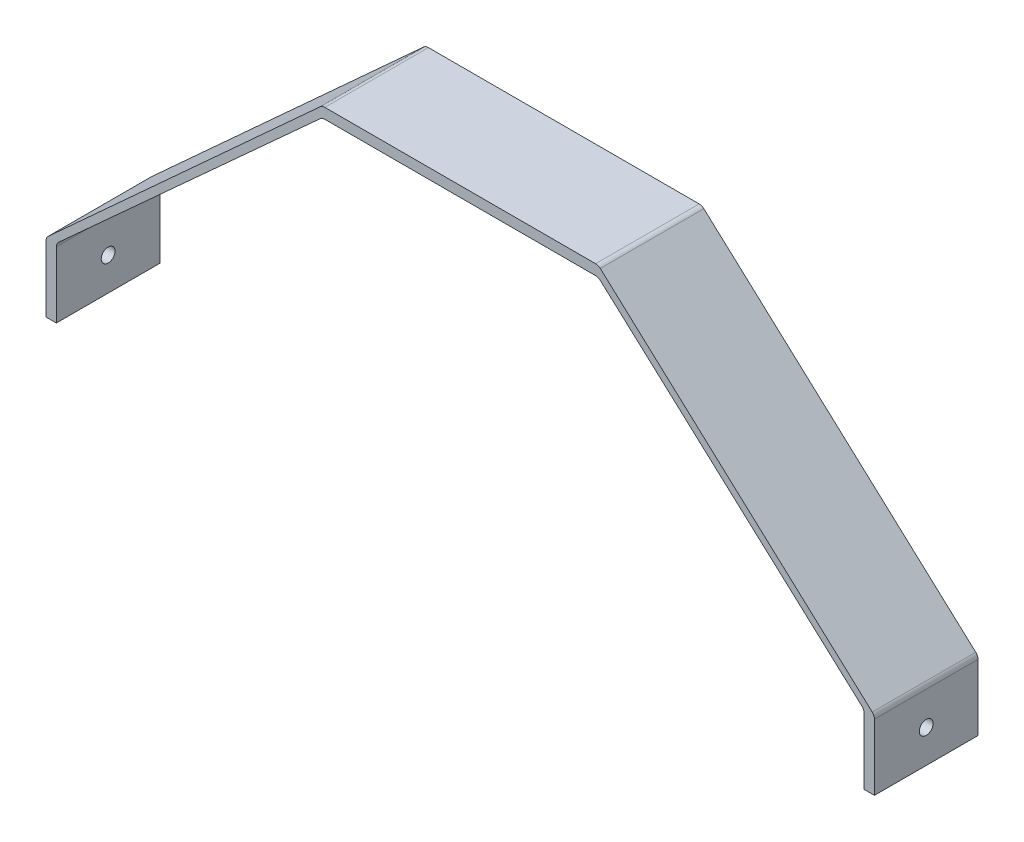
SolidWorks part; units mm, degrees
ref_plane "Front Plane" through (0, 0, 0) normal (0, 0, 1) x (1, 0, 0)
ref_plane "Top Plane" through (0, 0, 0) normal (0, 1, 0) x (1, 0, 0)
ref_plane "Right Plane" through (0, 0, 0) normal (1, 0, 0) x (0, 0, -1)
sketch "Sketch1" plane through (0, 0, 0) normal (0, 0, 1) x (1, 0, 0)
  line L0 (0, -1.905) -> (0, -116.205) construction
  line L1 (-50.8, -1.905) -> (50.8, -1.905)
  line L3 (-50.8, 1.905) -> (50.8, 1.905)
  line L5 (-50.8, -1.905) -> (50.8, 1.905) construction
  line L6 (-50.8, 1.905) -> (50.8, -1.905) construction
  line L7 (-152.4, -116.205) -> (152.4, -116.205) construction
  line L8 (50.8, 1.905) -> (152.4, -90.805)
  line L9 (152.4, -116.205) -> (148.59, -116.205)
  line L10 (152.4, -116.205) -> (152.4, -90.805)
  line L12 (148.59, -116.205) -> (148.59, -90.805)
  line L13 (-152.4, -116.205) -> (-148.59, -116.205)
  line L14 (-152.4, -116.205) -> (-152.4, -90.805)
  line L16 (-148.59, -116.205) -> (-148.59, -90.805)
  line L17 (50.8, -1.905) -> (148.59, -90.805)
  line L18 (-148.59, -90.805) -> (-50.8, -1.905)
  line L19 (-152.4, -90.805) -> (-50.8, 1.905)
  line L20 (148.59, -90.805) -> (152.4, -90.805) construction
  line L21 (50.8, -1.905) -> (50.8, 1.905) construction
  line L22 (-50.8, -1.905) -> (-50.8, 1.905) construction
  line L23 (-152.4, -90.805) -> (-148.59, -90.805) construction
  point P0 (0, 0)
  dimension "D1" = 3.81
  dimension "D2" = 101.6
  dimension "D3" = 114.3
  dimension "D4" = 304.8
  dimension "D5" = 3.81
  dimension "D6" = 25.4
extrude "Boss-Extrude1" add sketch "Sketch1" against normal blind 38.1
fillet "Fillet1" radius 2.54 8 edges at (50.8, -1.905, -19.05) (50.8, 1.905, -19.05) (152.4, -90.805, -19.05) (148.59, -90.805, -19.05) (-148.59, -90.805, -19.05) (-152.4, -90.805, -19.05) (-50.8, -1.905, -19.05) (-50.8, 1.905, -19.05)
sketch "Sketch2" plane through (152.4, 0, 0) normal (1, 0, 0) x (0, 0, -1)
  line L0 (0, -91.9258) -> (38.1, -116.205) construction
  circle A0 centre (19.05, -104.0654) radius 2.54
  dimension "D1" = 5.08
extrude "Cut-Extrude1" cut sketch "Sketch2" against normal through all
